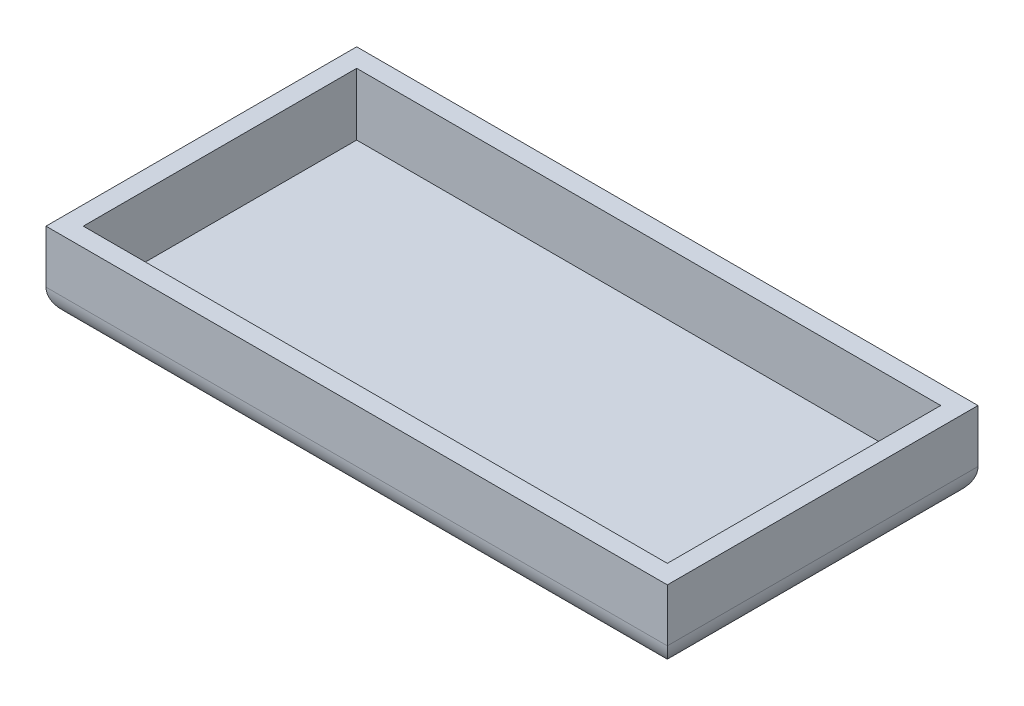
SolidWorks part; units mm, degrees
ref_plane "Front Plane" through (0, 0, 0) normal (0, 0, 1) x (1, 0, 0)
ref_plane "Top Plane" through (0, 0, 0) normal (0, 1, 0) x (1, 0, 0)
ref_plane "Right Plane" through (0, 0, 0) normal (1, 0, 0) x (0, 0, -1)
sketch "Sketch1" plane through (0, 0, 0) normal (0, 1, 0) x (1, 0, 0)
  line L1 (-2000, -1000) -> (2000, -1000)
  line L2 (-2000, -1000) -> (-2000, 1000)
  line L3 (-2000, 1000) -> (2000, 1000)
  line L4 (2000, -1000) -> (2000, 1000)
  line L5 (0, 1000) -> (0, -1000) construction
  line L6 (-2000, 0) -> (2000, 0) construction
  line L11 (0, 880) -> (0, -880) construction
  line L12 (-1880, 0) -> (1880, 0) construction
  point P0 (0, 0)
  point P4 (0, 0)
  dimension "D1" = 4000
  dimension "D2" = 2000
extrude "Boss-Extrude2" add sketch "Sketch1" along normal blind 120
sketch "Sketch2" plane through (0, 120, 0) normal (0, 1, 0) x (1, 0, 0)
  line L0 (2000, 1000) -> (-2000, 1000) construction
  line L1 (-1880, -880) -> (1880, -880)
  line L2 (-1880, -880) -> (-1880, 880)
  line L3 (-1880, 880) -> (1880, 880)
  line L4 (1880, -880) -> (1880, 880)
  line L5 (0, 880) -> (0, -880) construction
  line L6 (-1880, 0) -> (1880, 0) construction
  line L7 (-2000, 1000) -> (-2000, -1000) construction
  line L8 (-2000, 1000) -> (-2000, -1000)
  line L9 (2000, 1000) -> (-2000, 1000)
  line L10 (2000, -1000) -> (2000, 1000) construction
  line L11 (-2000, -1000) -> (2000, -1000) construction
  line L12 (2000, -1000) -> (2000, 1000)
  line L13 (-2000, -1000) -> (2000, -1000)
  point P0 (0, 0)
  dimension "D1" = 120
  dimension "D2" = 120
extrude "Boss-Extrude3" add sketch "Sketch2" along normal blind 400
fillet "Fillet1" radius 180 4 edges at (-2000, 0, 0) (0, 0, 1000) (2000, 0, 0) (0, 0, -1000)
